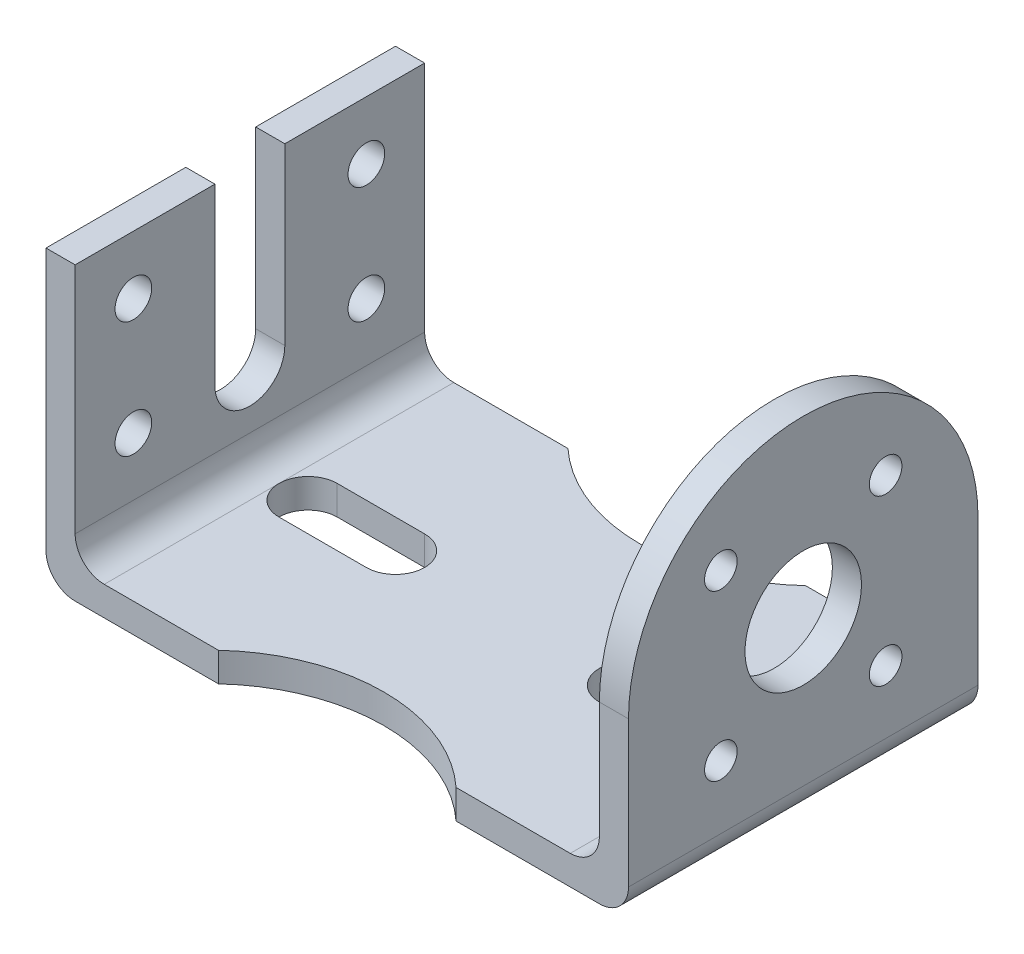
SolidWorks part; units mm, degrees
ref_plane "Alzado" through (0, 0, 0) normal (0, 0, 1) x (1, 0, 0)
ref_plane "Planta" through (0, 0, 0) normal (0, 1, 0) x (1, 0, 0)
ref_plane "Vista lateral" through (0, 0, 0) normal (1, 0, 0) x (0, 0, -1)
sketch "Croquis1" plane through (0, 0, 0) normal (0, 1, 0) x (1, 0, 0)
  line L0 (-1.1834, 21.0412) -> (-1.1834, 13.0412) construction
  line L1 (-46.4208, 21.0412) -> (-16.8169, 21.0412)
  line L2 (-46.4208, 21.0412) -> (-46.4208, -38.9588)
  line L3 (-46.4208, -38.9588) -> (-16.8169, -38.9588)
  line L4 (53.5792, 21.0412) -> (53.5792, -38.9588)
  line L5 (-1.1834, 13.0412) -> (3.5792, 13.0412) construction
  line L6 (3.5792, 13.0412) -> (3.5792, 73.0412) construction
  line L7 (23.9753, 21.0412) -> (53.5792, 21.0412)
  line L8 (3.5792, -8.9588) -> (-16.4208, -8.9588) construction
  line L9 (23.9753, -38.9588) -> (53.5792, -38.9588)
  line L10 (3.5792, 21.0412) -> (3.5792, -38.9588) construction
  line L11 (-16.4208, -3.9588) -> (-31.4208, -3.9588)
  line L12 (-16.4208, -13.9588) -> (-31.4208, -13.9588)
  line L13 (23.5792, -13.9588) -> (38.5792, -13.9588)
  line L14 (23.5792, -3.9588) -> (38.5792, -3.9588)
  arc A0 (-16.8169, 21.0412) -> (23.9753, 21.0412) centre (3.5792, 43.0412) ccw
  arc A1 (-16.8169, -38.9588) -> (23.9753, -38.9588) centre (3.5792, -60.9588) cw
  arc A2 (-16.4208, -13.9588) -> (-16.4208, -3.9588) centre (-16.4208, -8.9588) ccw
  arc A3 (-31.4208, -3.9588) -> (-31.4208, -13.9588) centre (-31.4208, -8.9588) ccw
  arc A4 (38.5792, -3.9588) -> (38.5792, -13.9588) centre (38.5792, -8.9588) cw
  arc A5 (23.5792, -13.9588) -> (23.5792, -3.9588) centre (23.5792, -8.9588) cw
  dimension "D6" = 10
  dimension "D1" = 100
  dimension "D2" = 60
  dimension "D3" = 8
  dimension "D4" = 60
  dimension "D5" = 20
  dimension "D7" = 15
extrude "Saliente-Extruir1" add sketch "Croquis1" along normal blind 5
sketch "Croquis2" plane through (53.5792, 0, 0) normal (1, 0, 0) x (0, 0, -1)
  line L0 (-8.9588, 60) -> (-8.9588, 0) construction
  line L1 (-38.9588, 0) -> (21.0412, 0)
  line L2 (-38.9588, 0) -> (-38.9588, 30)
  line L4 (21.0412, 0) -> (21.0412, 30)
  line L5 (-38.9588, 30) -> (21.0412, 30) construction
  line L6 (-8.9588, 30) -> (-23.1009, 44.1421) construction
  line L7 (-8.9588, 30) -> (-23.1009, 15.8579) construction
  circle A0 centre (-8.9588, 30) radius 10
  arc A1 (21.0412, 30) -> (-38.9588, 30) centre (-8.9588, 30) ccw
  circle A2 centre (-23.1009, 44.1421) radius 2.8
  circle A3 centre (-23.1009, 15.8579) radius 2.8
  circle A4 centre (5.1834, 15.8579) radius 2.8
  circle A5 centre (5.1834, 44.1421) radius 2.8
  dimension "D3" = 20
  dimension "D2" = 5.6
  dimension "D4" = 5.6
  dimension "D1" = 60
extrude "Saliente-Extruir2" add sketch "Croquis2" against normal blind 5
sketch "Croquis3" plane through (-46.4208, 0, 0) normal (-1, 0, 0) x (0, 0, 1)
  line L0 (8.9588, 50) -> (8.9588, 20) construction
  line L1 (-21.0412, 0) -> (38.9588, 0)
  line L2 (-21.0412, 0) -> (-21.0412, 50)
  line L3 (-21.0412, 50) -> (2.9588, 50)
  line L4 (38.9588, 0) -> (38.9588, 50)
  line L5 (2.9588, 20) -> (2.9588, 50)
  line L6 (14.9588, 20) -> (14.9588, 50)
  line L7 (8.9588, 20) -> (-11.0412, 20) construction
  line L8 (-11.0412, 20) -> (-11.0412, 40) construction
  line L9 (14.9588, 50) -> (38.9588, 50)
  arc A0 (2.9588, 20) -> (14.9588, 20) centre (8.9588, 20) ccw
  circle A1 centre (-11.0412, 20) radius 3.15
  circle A2 centre (-11.0412, 40) radius 3.15
  circle A3 centre (28.9588, 20) radius 3.15
  circle A4 centre (28.9588, 40) radius 3.15
  dimension "D4" = 12
  dimension "D6" = 6.3
  dimension "D8" = 6.3
  dimension "D1" = 60
  dimension "D2" = 50
  dimension "D3" = 30
  dimension "D5" = 20
  dimension "D7" = 20
extrude "Saliente-Extruir3" add sketch "Croquis3" against normal blind 5
fillet "Redondeo1" radius 5 1 edges at (-41.4208, 5, 8.9588)
fillet "Redondeo2" radius 5 1 edges at (48.5792, 5, 8.9588)
fillet "Redondeo3" radius 5 1 edges at (53.5792, 0, 8.9588)
fillet "Redondeo4" radius 5 1 edges at (-46.4208, 0, 8.9588)
